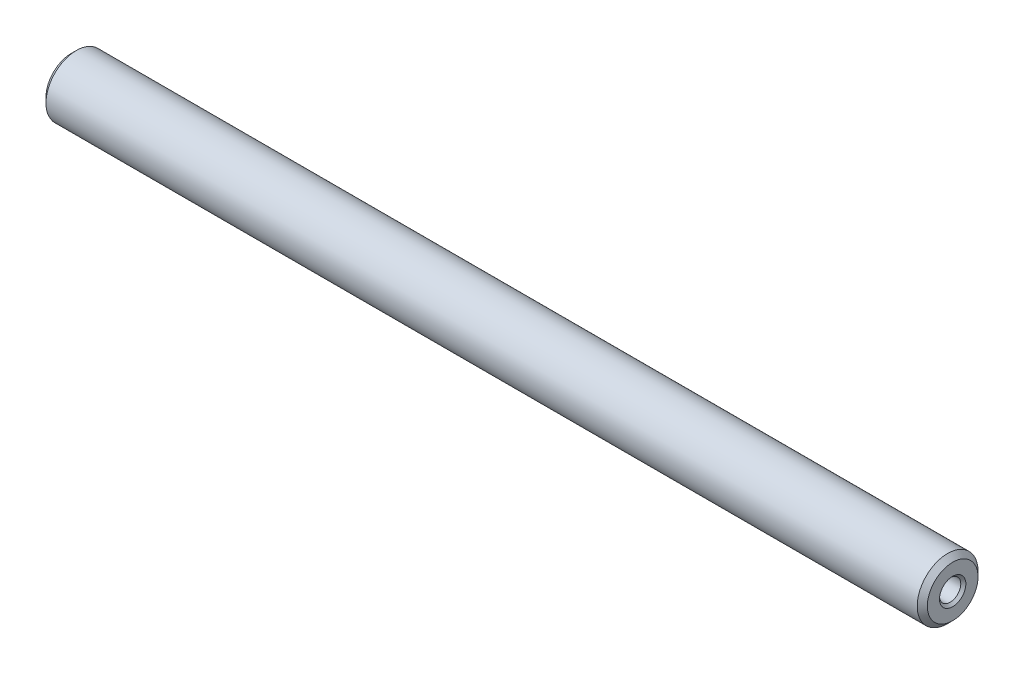
SolidWorks part; units mm, degrees
material "Chrome Stainless Steel"
ref_plane "Front Plane" through (0, 0, 0) normal (0, 0, 1) x (1, 0, 0)
ref_plane "Top Plane" through (0, 0, 0) normal (0, 1, 0) x (1, 0, 0)
ref_plane "Right Plane" through (0, 0, 0) normal (1, 0, 0) x (0, 0, -1)
sketch "Sketch1" plane through (0, 0, 0) normal (1, 0, 0) x (0, 0, -1)
  circle A0 centre (0, 0) radius 6
  dimension "D1" = 12
extrude "Boss-Extrude1" add sketch "Sketch1" along normal blind 174
chamfer "Chamfer1" distance 1 angle 45 2 edges at (174, 0, -6) (0, 0, -6)
hole_wizard "M5 Tapped Hole1" positions "Sketch3" profile "Sketch2" tap size "M5" standard "ISO"
sketch "Sketch3" plane through (174, 0, 0) normal (1, 0, 0) x (0, 0, -1)
  point P1 (0, 0)
sketch "Sketch2" plane through (174, 0, 0) normal (0, 1, 0) x (0, 0, -1)
  line L0 (0, 0) -> (0, 15.2618)
  line L1 (0, 15.2618) -> (2.1, 14)
  line L2 (2.1, 14) -> (2.1, 0)
  line L5 (2.1, 0) -> (0, 0)
  line L10 (0, 15.2618) -> (-2.1, 14) construction
  line L11 (0, -6.35) -> (0, 107.95) construction
  dimension "Tap Drill Dia." = 4.2
  dimension "Tap Drill Depth" = 14
  dimension "Drill Angle" = 118
cosmetic thread "Hole Thread1" parameters "D1"=10, "D2"=5
chamfer "Chamfer2" distance 0.5 angle 45 1 edges at (174, 0, -2.1)
hole_wizard "M5 Tapped Hole2" positions "Sketch5" profile "Sketch4" tap size "M5" standard "ISO"
sketch "Sketch5" plane through (0, 0, 0) normal (-1, 0, 0) x (0, 0, 1)
  point P1 (0, 0)
sketch "Sketch4" plane through (0, 0, 0) normal (0, 1, 0) x (0, 0, 1)
  line L0 (0, 0) -> (0, 15.2618)
  line L1 (0, 15.2618) -> (2.1, 14)
  line L2 (2.1, 14) -> (2.1, 0)
  line L5 (2.1, 0) -> (0, 0)
  line L10 (0, 15.2618) -> (-2.1, 14) construction
  line L11 (0, -6.35) -> (0, 107.95) construction
  dimension "Tap Drill Dia." = 4.2
  dimension "Tap Drill Depth" = 14
  dimension "Drill Angle" = 118
cosmetic thread "Hole Thread2" parameters "D1"=10, "D2"=5
chamfer "Chamfer3" distance 0.5 angle 45 1 edges at (0, 0, 2.1)
